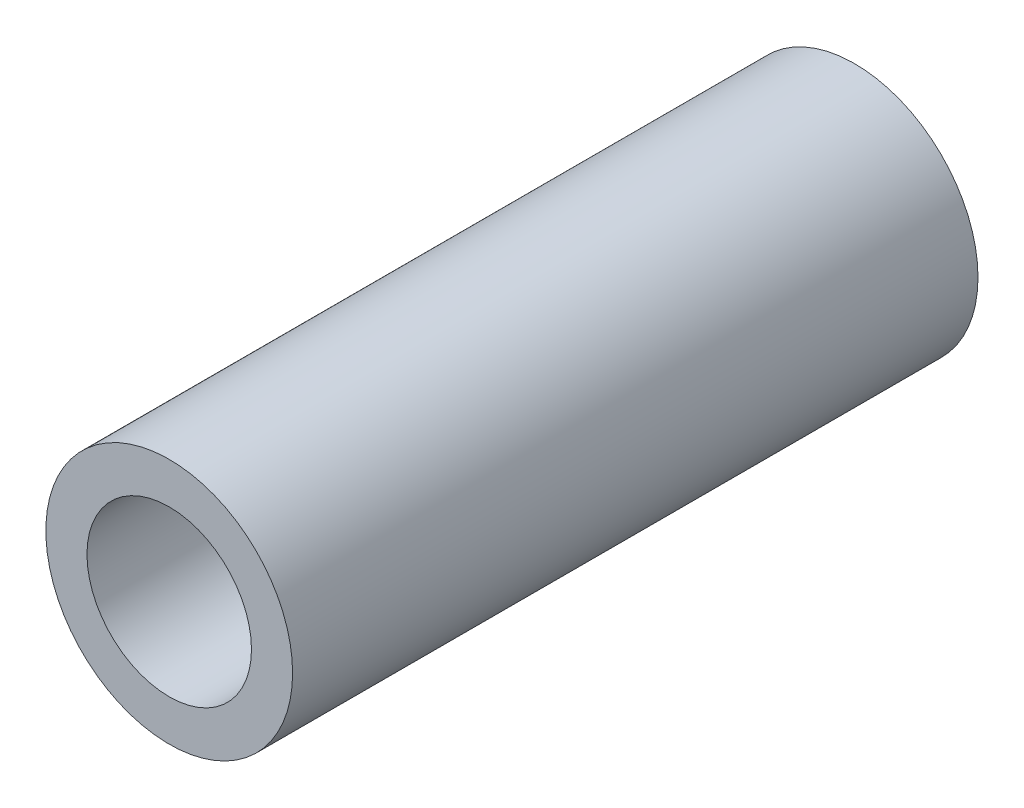
SolidWorks part; units mm, degrees
ref_plane "Płaszczyzna przednia" through (0, 0, 0) normal (0, 0, 1) x (1, 0, 0)
ref_plane "Płaszczyzna górna" through (0, 0, 0) normal (0, 1, 0) x (1, 0, 0)
ref_plane "Płaszczyzna prawa" through (0, 0, 0) normal (1, 0, 0) x (0, 0, -1)
sketch "Szkic1" plane through (0, 0, 0) normal (0, 0, 1) x (1, 0, 0)
  circle A0 centre (0, 0) radius 9
  circle A1 centre (0, 0) radius 6
  dimension "D1" = 12
  dimension "D2" = 18
extrude "Dodanie-wyciągnięcie1" add sketch "Szkic1" along normal blind 50
